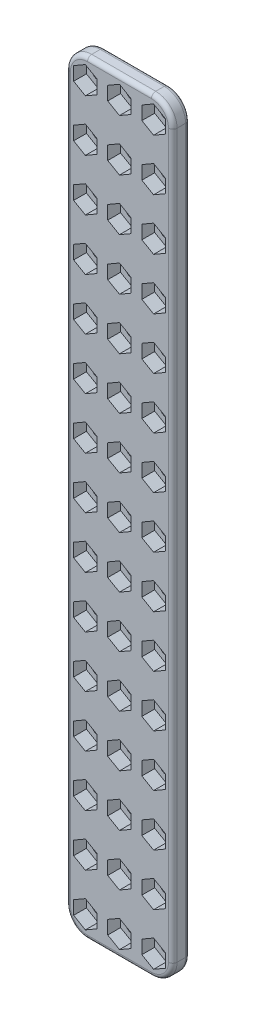
SolidWorks part; units mm, degrees
ref_plane "Front Plane" through (0, 0, 0) normal (0, 0, 1) x (1, 0, 0)
ref_plane "Top Plane" through (0, 0, 0) normal (0, 1, 0) x (1, 0, 0)
ref_plane "Right Plane" through (0, 0, 0) normal (1, 0, 0) x (0, 0, -1)
sketch "草图1" plane through (0, 0, 0) normal (0, 0, 1) x (1, 0, 0)
  line L1 (-12.5, 5) -> (12.5, 5)
  line L2 (-12.5, 5) -> (-12.5, -5)
  line L3 (-12.5, -5) -> (12.5, -5)
  line L4 (12.5, 5) -> (12.5, -5)
  line L5 (-12.5, 5) -> (12.5, -5) construction
  line L6 (-12.5, -5) -> (12.5, 5) construction
  point P0 (0, 0)
  dimension "D1" = 25
  dimension "D2" = 10
extrude "凸台-拉伸1" add sketch "草图1" along normal blind 4
sketch "草图2" plane through (0, 0, 4) normal (0, 0, 1) x (1, 0, 0)
  line L0 (0, -1000) -> (0, 49000) construction
  circle A0 centre (0, 0) radius 1.5
  circle A1 centre (-8, 0) radius 1.5
  circle A2 centre (8, 0) radius 1.5
  dimension "D1" = 3
  dimension "D2" = 3
  dimension "D3" = 16
sketch "草图3" plane through (0, 0, 4) normal (0, 0, 1) x (1, 0, 0)
  line L19 (-8, 3.1754) -> (-10.75, 1.5877)
  line L20 (-10.75, 1.5877) -> (-10.75, -1.5877)
  line L21 (-10.75, -1.5877) -> (-8, -3.1754)
  line L22 (-8, -3.1754) -> (-5.25, -1.5877)
  line L23 (-5.25, -1.5877) -> (-5.25, 1.5877)
  line L24 (-5.25, 1.5877) -> (-8, 3.1754)
  line L25 (0, 3.1754) -> (-2.75, 1.5877)
  line L26 (-2.75, 1.5877) -> (-2.75, -1.5877)
  line L27 (-2.75, -1.5877) -> (0, -3.1754)
  line L28 (0, -3.1754) -> (2.75, -1.5877)
  line L29 (2.75, -1.5877) -> (2.75, 1.5877)
  line L30 (2.75, 1.5877) -> (0, 3.1754)
  line L31 (8, 3.1754) -> (5.25, 1.5877)
  line L32 (5.25, 1.5877) -> (5.25, -1.5877)
  line L33 (5.25, -1.5877) -> (8, -3.1754)
  line L34 (8, -3.1754) -> (10.75, -1.5877)
  line L35 (10.75, -1.5877) -> (10.75, 1.5877)
  line L36 (10.75, 1.5877) -> (8, 3.1754)
  circle A1 centre (-8, 0) radius 2.75 construction
  circle A2 centre (0, 0) radius 2.75 construction
  circle A3 centre (8, 0) radius 2.75 construction
  dimension "D1" = 5.5
extrude "切除-拉伸1" cut sketch "草图2" against normal through all
extrude "切除-拉伸2" cut sketch "草图3" against normal blind 3
sketch "草图4" plane through (0, 0, 4) normal (0, 0, 1) x (1, 0, 0)
  line L0 (0, -1000) -> (0, 49000) construction
  line L1 (-1000, 0) -> (49000, 0) construction
  line L2 (-1000, -12.1) -> (49000, -12.1) construction
  line L4 (-12.5, -5) -> (12.5, -5)
  line L5 (-12.5, -5) -> (-12.5, -17.1)
  line L6 (-12.5, -17.1) -> (12.5, -17.1)
  line L7 (12.5, -5) -> (12.5, -17.1)
  dimension "D1" = 12.1
  dimension "D2" = 12.1
extrude "凸台-拉伸2" add sketch "草图4" against normal up to surface (4 mm away) contours L5 L6 L7 L4 up to face at (6.5, 0, 0)
sketch "草图5" plane through (0, 0, 4) normal (0, 0, 1) x (1, 0, 0)
  line L0 (0, -201000) -> (0, 249000) construction
  line L1 (-201000, -12.1) -> (249000, -12.1) construction
  line L2 (0, -1000) -> (0, 49000) construction
  circle A0 centre (0, -12.1) radius 1.5
  circle A1 centre (-8, -12.1) radius 1.5
  circle A2 centre (8, -12.1) radius 1.5
  dimension "D1" = 3
  dimension "D2" = 3
  dimension "D3" = 16
sketch "草图6" plane through (0, 0, 4) normal (0, 0, 1) x (1, 0, 0)
  line L1 (-8, -8.9246) -> (-10.75, -10.5123)
  line L2 (-10.75, -10.5123) -> (-10.75, -13.6877)
  line L3 (-10.75, -13.6877) -> (-8, -15.2754)
  line L4 (-8, -15.2754) -> (-5.25, -13.6877)
  line L5 (-5.25, -13.6877) -> (-5.25, -10.5123)
  line L6 (-5.25, -10.5123) -> (-8, -8.9246)
  line L7 (0, -8.9246) -> (-2.75, -10.5123)
  line L8 (-2.75, -10.5123) -> (-2.75, -13.6877)
  line L9 (-2.75, -13.6877) -> (0, -15.2754)
  line L10 (0, -15.2754) -> (2.75, -13.6877)
  line L11 (2.75, -13.6877) -> (2.75, -10.5123)
  line L12 (2.75, -10.5123) -> (0, -8.9246)
  line L13 (8, -8.9246) -> (5.25, -10.5123)
  line L14 (5.25, -10.5123) -> (5.25, -13.6877)
  line L15 (5.25, -13.6877) -> (8, -15.2754)
  line L16 (8, -15.2754) -> (10.75, -13.6877)
  line L17 (10.75, -13.6877) -> (10.75, -10.5123)
  line L18 (10.75, -10.5123) -> (8, -8.9246)
  circle A0 centre (-8, -12.1) radius 2.75 construction
  circle A1 centre (0, -12.1) radius 2.75 construction
  circle A2 centre (8, -12.1) radius 2.75 construction
  dimension "D1" = 5.5
extrude "切除-拉伸3" cut sketch "草图5" against normal through all
extrude "切除-拉伸4" cut sketch "草图6" against normal blind 3
pattern_linear "阵列(线性)1" count 14 spacing 12.1 along (0, -1, 0) of "切除-拉伸4", "切除-拉伸3", "凸台-拉伸2"
fillet "圆角1" radius 5 4 edges at (12.5, 5, 2) (-12.5, 5, 2) (12.5, -174.4, 2) (-12.5, -174.4, 2)
fillet "圆角2" radius 1 16 edges at (11.0355, 3.5355, 4) (11.0355, 3.5355, 0) (12.5, -84.7, 0) (12.5, -84.7, 4) (-12.5, -84.7, 4) (-12.5, -84.7, 0) (-11.0355, 3.5355, 4) (-11.0355, 3.5355, 0) (0, 5, 4) (0, 5, 0) (11.0355, -172.9355, 0) (11.0355, -172.9355, 4) (0, -174.4, 4) (-11.0355, -172.9355, 0) (-11.0355, -172.9355, 4) (0, -174.4, 0)
